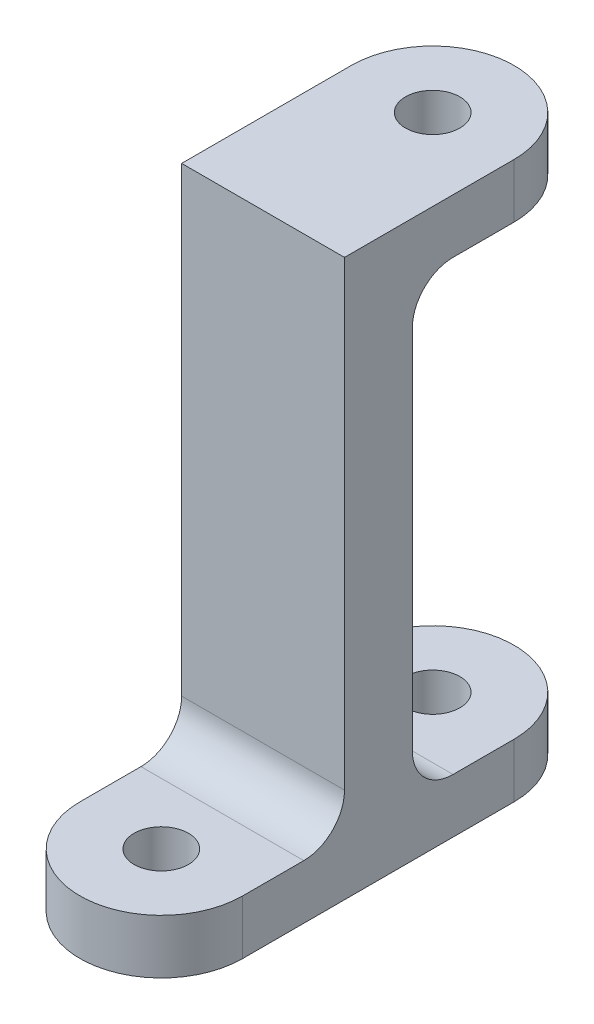
SolidWorks part; units mm, degrees
ref_plane "Front Plane" through (0, 0, 0) normal (0, 0, 1) x (1, 0, 0)
ref_plane "Top Plane" through (0, 0, 0) normal (0, 1, 0) x (1, 0, 0)
ref_plane "Right Plane" through (0, 0, 0) normal (1, 0, 0) x (0, 0, -1)
sketch "Sketch1" plane through (0, 0, 0) normal (0, 1, 0) x (1, 0, 0)
  line L0 (0, 20) -> (0, 0) construction
  line L1 (-6, 20) -> (-6, 0)
  line L2 (6, 20) -> (6, 0)
  circle A0 centre (0, 0) radius 2
  circle A1 centre (0, 20) radius 2
  circle A2 centre (0, 20) radius 6
  circle A3 centre (0, 0) radius 6
  dimension "D1" = 4
  dimension "D2" = 4
  dimension "D3" = 4
  dimension "D4" = 4
  dimension "D5" = 20
extrude "Boss-Extrude1" add sketch "Sketch1" along normal blind 4
sketch "Sketch2" plane through (0, 4, 0) normal (0, 1, 0) x (1, 0, 0)
  line L0 (-6, 20) -> (6, 0) construction
  line L1 (-6, 20) -> (-6, 0) construction
  line L2 (6, 12.5) -> (-6, 12.5)
  line L3 (6, 12.5) -> (6, 7.5)
  line L4 (6, 7.5) -> (-6, 7.5)
  line L5 (-6, 12.5) -> (-6, 7.5)
  line L6 (6, 12.5) -> (-6, 7.5) construction
  line L7 (6, 7.5) -> (-6, 12.5) construction
  point P4 (0, 10)
  dimension "D1" = 5
extrude "Boss-Extrude2" add sketch "Sketch2" along normal blind 33 contours L3 L2 L5 L4
sketch "Sketch3" plane through (0, 37, 0) normal (0, 1, 0) x (1, 0, 0)
  line L3 (-6, 12.5) -> (6, 12.5)
  line L4 (-6, 7.5) -> (6, 7.5)
  line L5 (6, 7.5) -> (6, 12.5)
  line L6 (6, 12.5) -> (-6, 12.5)
  line L7 (-6, 12.5) -> (-6, 7.5)
  line L8 (-6, 7.5) -> (6, 7.5)
  line L9 (6, 7.5) -> (6, 12.5)
  line L10 (6, 12.5) -> (-6, 12.5)
  line L11 (-6, 12.5) -> (-6, 7.5)
  line L12 (6, 12.5) -> (6, 20)
  line L13 (-6, 20) -> (-6, 12.5)
  line L14 (-6, 12.5) -> (6, 12.5)
  line L15 (6, 12.5) -> (6, 20)
  line L16 (-6, 20) -> (-6, 12.5)
  circle A0 centre (0, 20) radius 2
  arc A1 (6, 20) -> (-6, 20) centre (0, 20) ccw
  arc A2 (6, 20) -> (-6, 20) centre (0, 20) ccw
  line M9 (-6, 7.5) -> (6, 7.5)
  line M10 (6, 7.5) -> (6, 12.5)
  line M11 (6, 12.5) -> (-6, 12.5)
  line M12 (-6, 12.5) -> (-6, 7.5)
  dimension "D1" = 0
  dimension "D2" = 0
extrude "Boss-Extrude3" add sketch "Sketch3" along normal blind 4 contours L15 A2 L16 A0 M11 | M12 M9 M10 M11
fillet "Fillet1" radius 3 3 edges at (0, 37, -12.5) (0, 4, -7.5) (0, 4, -12.5)
